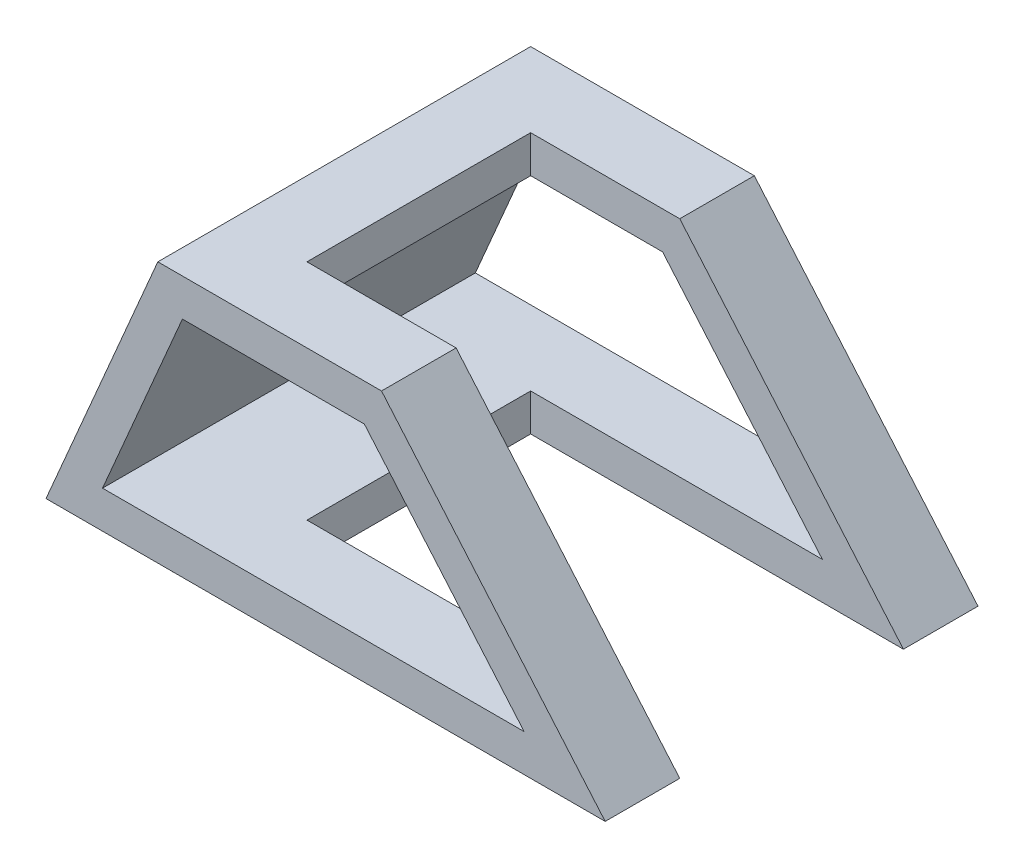
SolidWorks part; units mm, degrees
ref_plane "Front Plane" through (0, 0, 0) normal (0, 0, 1) x (1, 0, 0)
ref_plane "Top Plane" through (0, 0, 0) normal (0, 1, 0) x (1, 0, 0)
ref_plane "Right Plane" through (0, 0, 0) normal (1, 0, 0) x (0, 0, -1)
sketch "Sketch1" plane through (0, 0, 0) normal (0, 0, 1) x (1, 0, 0)
  line L0 (0, 0) -> (30, 70)
  line L1 (30, 70) -> (90, 70)
  line L2 (90, 70) -> (150, 0)
  line L3 (150, 0) -> (0, 0)
  line L4 (15.1654, 10) -> (36.594, 60)
  line L5 (36.594, 60) -> (85.4007, 60)
  line L6 (85.4007, 60) -> (128.2578, 10)
  line L7 (128.2578, 10) -> (15.1654, 10)
  dimension "D1" = 150
  dimension "D2" = 70
  dimension "D3" = 30
  dimension "D4" = 60
  dimension "D5" = 10
extrude "Boss-Extrude1" add sketch "Sketch1" along normal mid plane 100
sketch "Sketch2" plane through (0, 0, 0) normal (0, 1, 0) x (1, 0, 0)
  line L0 (90, 50) -> (90, -50) construction
  line L1 (90, -50) -> (90, 50) construction
  line L2 (150, -50) -> (150, 50) construction
  line L3 (150, -30) -> (50, -30)
  line L4 (150, -30) -> (150, 30)
  line L5 (150, 30) -> (50, 30)
  line L6 (50, -30) -> (50, 30)
  line L7 (150, 50) -> (90, 50) construction
  dimension "D1" = 100
  dimension "D2" = 60
  dimension "D3" = 20
extrude "Cut-Extrude1" cut sketch "Sketch2" along normal through all
